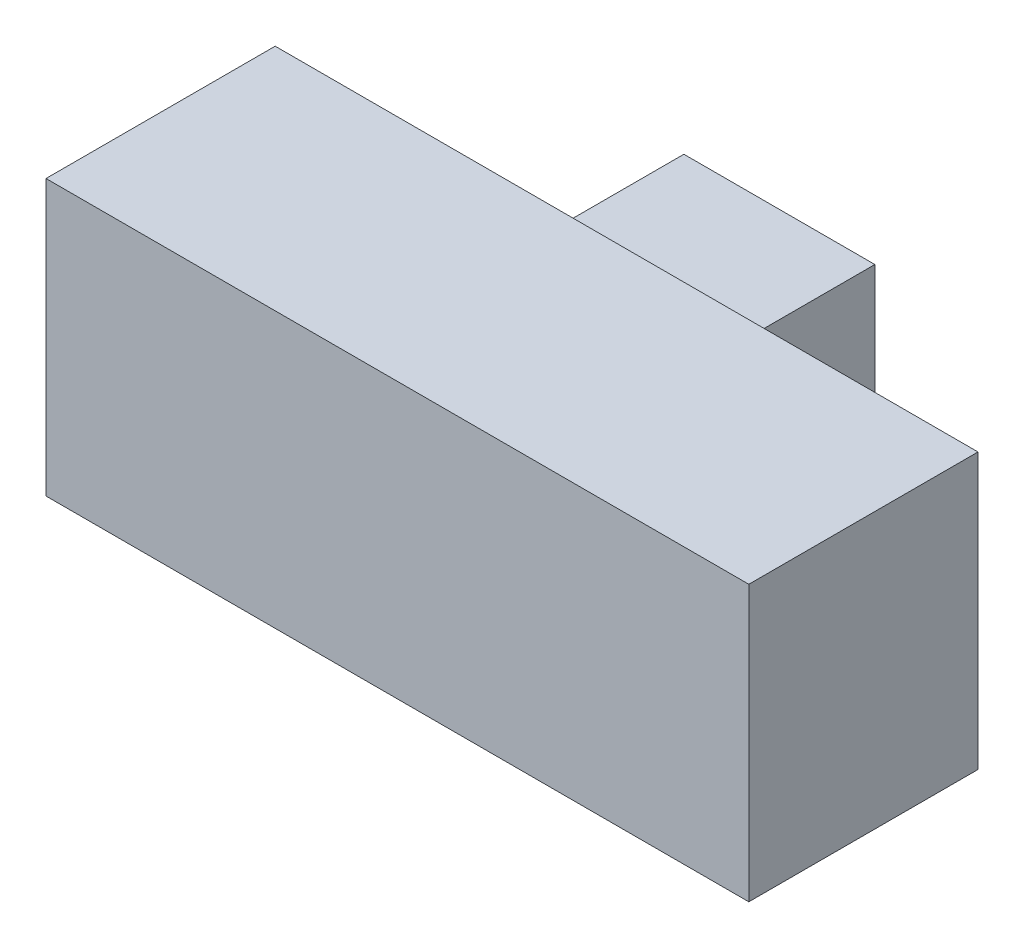
SolidWorks part; units mm, degrees
ref_plane "Front Plane" through (0, 0, 0) normal (0, 0, 1) x (1, 0, 0)
ref_plane "Top Plane" through (0, 0, 0) normal (0, 1, 0) x (1, 0, 0)
ref_plane "Right Plane" through (0, 0, 0) normal (1, 0, 0) x (0, 0, -1)
sketch "Sketch1" plane through (0, 0, 0) normal (0, 0, 1) x (1, 0, 0)
  line L1 (-4.6, 1.8) -> (4.6, 1.8)
  line L2 (-4.6, 1.8) -> (-4.6, -1.8)
  line L3 (-4.6, -1.8) -> (4.6, -1.8)
  line L4 (4.6, 1.8) -> (4.6, -1.8)
  line L5 (-4.6, 1.8) -> (4.6, -1.8) construction
  line L6 (-4.6, -1.8) -> (4.6, 1.8) construction
  point P0 (0, 0)
  dimension "D1" = 9.2
  dimension "D2" = 3.6
extrude "Boss-Extrude1" add sketch "Sketch1" along normal blind 3
sketch "Sketch2" plane through (0, 0, 0) normal (0, 0, -1) x (-1, 0, 0)
  line L0 (4.6, 0) -> (-4.6, 0) construction
  line L1 (4.6, 1.8) -> (4.6, -1.8) construction
  line L2 (-4.6, -1.8) -> (-4.6, 1.8) construction
  line L4 (1.25, 1.25) -> (-1.25, 1.25)
  line L5 (1.25, 1.25) -> (1.25, -1.25)
  line L6 (1.25, -1.25) -> (-1.25, -1.25)
  line L7 (-1.25, 1.25) -> (-1.25, -1.25)
  line L8 (1.25, 1.25) -> (-1.25, -1.25) construction
  line L9 (1.25, -1.25) -> (-1.25, 1.25) construction
  point P6 (0, 0)
  dimension "D1" = 2.5
  dimension "D2" = 2.5
extrude "Boss-Extrude2" add sketch "Sketch2" along normal blind 2
